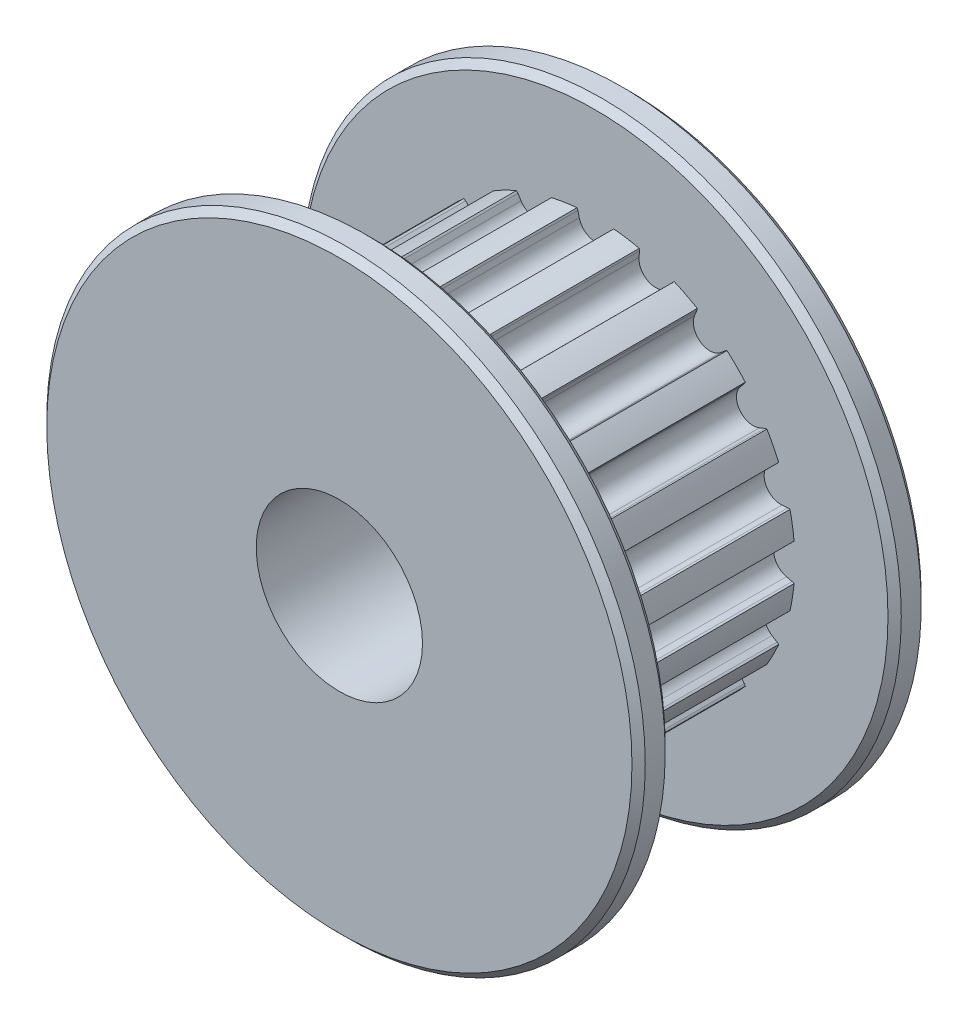
SolidWorks part; units mm, degrees
ref_plane "Спереди" through (0, 0, 0) normal (0, 0, 1) x (1, 0, 0)
ref_plane "Сверху" through (0, 0, 0) normal (0, 1, 0) x (1, 0, 0)
ref_plane "Справа" through (0, 0, 0) normal (1, 0, 0) x (0, 0, -1)
ref_plane "Плоскость1" through (0, 0, 0) normal (0, -1, 0) x (1, 0, 0)
sketch "Эскиз1" plane through (0, 0, 0) normal (0, -1, 0) x (1, 0, 0)
  line L0 (9, -3.35) -> (0, -3.35)
  line L1 (0, -3.35) -> (0, -4.35)
  line L2 (0, -4.35) -> (9, -4.35)
  line L3 (9, -4.35) -> (9, -3.35)
  line L4 (0, -3.35) -> (0, -4.35) construction
revolve "Повернуть1" add sketch "Эскиз1" angle 360 about L4
sketch "Эскиз2" plane through (0, 0, -3.35) normal (0, 0, 1) x (1, 0, 0)
  line L0 (5.4631, 2.3299) -> (5.3126, 2.2369)
  line L1 (5.6128, 1.313) -> (5.7893, 1.3262)
  line L2 (5.9157, 0.5277) -> (5.7438, 0.4857)
  line L3 (5.7438, -0.4857) -> (5.9157, -0.5277)
  line L4 (5.7893, -1.3262) -> (5.6128, -1.313)
  line L5 (5.3126, -2.2369) -> (5.4631, -2.3299)
  line L6 (5.0961, -3.0502) -> (4.9323, -2.9832)
  line L7 (4.3614, -3.7691) -> (4.4757, -3.9041)
  line L8 (3.9041, -4.4757) -> (3.7691, -4.3614)
  line L9 (2.9832, -4.9323) -> (3.0502, -5.0961)
  line L10 (2.3299, -5.4631) -> (2.2369, -5.3126)
  line L11 (1.313, -5.6128) -> (1.3262, -5.7893)
  line L12 (0.5277, -5.9157) -> (0.4857, -5.7438)
  line L13 (-0.4857, -5.7438) -> (-0.5277, -5.9157)
  line L14 (-1.3262, -5.7893) -> (-1.313, -5.6128)
  line L15 (-2.2369, -5.3126) -> (-2.3299, -5.4631)
  line L16 (-3.0502, -5.0961) -> (-2.9832, -4.9323)
  line L17 (-3.7691, -4.3614) -> (-3.9041, -4.4757)
  line L18 (-4.4757, -3.9041) -> (-4.3614, -3.7691)
  line L19 (-4.9323, -2.9832) -> (-5.0961, -3.0502)
  line L20 (-5.4631, -2.3299) -> (-5.3126, -2.2369)
  line L21 (-5.6128, -1.313) -> (-5.7893, -1.3262)
  line L22 (-5.9157, -0.5277) -> (-5.7438, -0.4857)
  line L23 (-5.7438, 0.4857) -> (-5.9157, 0.5277)
  line L24 (-5.7893, 1.3262) -> (-5.6128, 1.313)
  line L25 (-5.3126, 2.2369) -> (-5.4631, 2.3299)
  line L26 (-5.0961, 3.0502) -> (-4.9323, 2.9832)
  line L27 (-4.3614, 3.7691) -> (-4.4757, 3.9041)
  line L28 (-3.9041, 4.4757) -> (-3.7691, 4.3614)
  line L29 (-2.9832, 4.9323) -> (-3.0502, 5.0961)
  line L30 (-2.3299, 5.4631) -> (-2.2369, 5.3126)
  line L31 (-1.313, 5.6128) -> (-1.3262, 5.7893)
  line L32 (-0.5277, 5.9157) -> (-0.4857, 5.7438)
  line L33 (0.4857, 5.7438) -> (0.5277, 5.9157)
  line L34 (1.3262, 5.7893) -> (1.313, 5.6128)
  line L35 (2.2369, 5.3126) -> (2.3299, 5.4631)
  line L36 (3.0502, 5.0961) -> (2.9832, 4.9323)
  line L37 (3.7691, 4.3614) -> (3.9041, 4.4757)
  line L38 (4.4757, 3.9041) -> (4.3614, 3.7691)
  line L39 (4.9323, 2.9832) -> (5.0961, 3.0502)
  arc A0 (5.0961, 3.0502) -> (5.1583, 3.0647) centre (5.1719, 2.8652) cw
  arc A1 (5.1583, 3.0647) -> (5.5113, 2.3717) centre (0, 0) cw
  arc A2 (5.5113, 2.3717) -> (5.4631, 2.3299) centre (5.3579, 2.5001) cw
  arc A3 (5.3126, 2.2369) -> (5.6128, 1.313) centre (5.5756, 1.8116) ccw
  arc A4 (5.7893, 1.3262) -> (5.8528, 1.3207) centre (5.8041, 1.1267) cw
  arc A5 (5.8528, 1.3207) -> (5.9745, 0.5526) centre (0, 0) cw
  arc A6 (5.9745, 0.5526) -> (5.9157, 0.5277) centre (5.8683, 0.722) cw
  arc A7 (5.7438, 0.4857) -> (5.7438, -0.4857) centre (5.8625, 0) ccw
  arc A8 (5.9157, -0.5277) -> (5.9745, -0.5526) centre (5.8683, -0.722) cw
  arc A9 (5.9745, -0.5526) -> (5.8528, -1.3207) centre (0, 0) cw
  arc A10 (5.8528, -1.3207) -> (5.7893, -1.3262) centre (5.8041, -1.1267) cw
  arc A11 (5.6128, -1.313) -> (5.3126, -2.2369) centre (5.5756, -1.8116) ccw
  arc A12 (5.4631, -2.3299) -> (5.5113, -2.3717) centre (5.3579, -2.5001) cw
  arc A13 (5.5113, -2.3717) -> (5.1583, -3.0647) centre (0, 0) cw
  arc A14 (5.1583, -3.0647) -> (5.0961, -3.0502) centre (5.1719, -2.8652) cw
  arc A15 (4.9323, -2.9832) -> (4.3614, -3.7691) centre (4.7429, -3.4459) ccw
  arc A16 (4.4757, -3.9041) -> (4.5087, -3.9588) centre (4.3231, -4.0334) cw
  arc A17 (4.5087, -3.9588) -> (3.9588, -4.5087) centre (0, 0) cw
  arc A18 (3.9588, -4.5087) -> (3.9041, -4.4757) centre (4.0334, -4.3231) cw
  arc A19 (3.7691, -4.3614) -> (2.9832, -4.9323) centre (3.4459, -4.7429) ccw
  arc A20 (3.0502, -5.0961) -> (3.0647, -5.1583) centre (2.8652, -5.1719) cw
  arc A21 (3.0647, -5.1583) -> (2.3717, -5.5113) centre (0, 0) cw
  arc A22 (2.3717, -5.5113) -> (2.3299, -5.4631) centre (2.5001, -5.3579) cw
  arc A23 (2.2369, -5.3126) -> (1.313, -5.6128) centre (1.8116, -5.5756) ccw
  arc A24 (1.3262, -5.7893) -> (1.3207, -5.8528) centre (1.1267, -5.8041) cw
  arc A25 (1.3207, -5.8528) -> (0.5526, -5.9745) centre (0, 0) cw
  arc A26 (0.5526, -5.9745) -> (0.5277, -5.9157) centre (0.722, -5.8683) cw
  arc A27 (0.4857, -5.7438) -> (-0.4857, -5.7438) centre (0, -5.8625) ccw
  arc A28 (-0.5277, -5.9157) -> (-0.5526, -5.9745) centre (-0.722, -5.8683) cw
  arc A29 (-0.5526, -5.9745) -> (-1.3207, -5.8528) centre (0, 0) cw
  arc A30 (-1.3207, -5.8528) -> (-1.3262, -5.7893) centre (-1.1267, -5.8041) cw
  arc A31 (-1.313, -5.6128) -> (-2.2369, -5.3126) centre (-1.8116, -5.5756) ccw
  arc A32 (-2.3299, -5.4631) -> (-2.3717, -5.5113) centre (-2.5001, -5.3579) cw
  arc A33 (-2.3717, -5.5113) -> (-3.0647, -5.1583) centre (0, 0) cw
  arc A34 (-3.0647, -5.1583) -> (-3.0502, -5.0961) centre (-2.8652, -5.1719) cw
  arc A35 (-2.9832, -4.9323) -> (-3.7691, -4.3614) centre (-3.4459, -4.7429) ccw
  arc A36 (-3.9041, -4.4757) -> (-3.9588, -4.5087) centre (-4.0334, -4.3231) cw
  arc A37 (-3.9588, -4.5087) -> (-4.5087, -3.9588) centre (0, 0) cw
  arc A38 (-4.5087, -3.9588) -> (-4.4757, -3.9041) centre (-4.3231, -4.0334) cw
  arc A39 (-4.3614, -3.7691) -> (-4.9323, -2.9832) centre (-4.7429, -3.4459) ccw
  arc A40 (-5.0961, -3.0502) -> (-5.1583, -3.0647) centre (-5.1719, -2.8652) cw
  arc A41 (-5.1583, -3.0647) -> (-5.5113, -2.3717) centre (0, 0) cw
  arc A42 (-5.5113, -2.3717) -> (-5.4631, -2.3299) centre (-5.3579, -2.5001) cw
  arc A43 (-5.3126, -2.2369) -> (-5.6128, -1.313) centre (-5.5756, -1.8116) ccw
  arc A44 (-5.7893, -1.3262) -> (-5.8528, -1.3207) centre (-5.8041, -1.1267) cw
  arc A45 (-5.8528, -1.3207) -> (-5.9745, -0.5526) centre (0, 0) cw
  arc A46 (-5.9745, -0.5526) -> (-5.9157, -0.5277) centre (-5.8683, -0.722) cw
  arc A47 (-5.7438, -0.4857) -> (-5.7438, 0.4857) centre (-5.8625, 0) ccw
  arc A48 (-5.9157, 0.5277) -> (-5.9745, 0.5526) centre (-5.8683, 0.722) cw
  arc A49 (-5.9745, 0.5526) -> (-5.8528, 1.3207) centre (0, 0) cw
  arc A50 (-5.8528, 1.3207) -> (-5.7893, 1.3262) centre (-5.8041, 1.1267) cw
  arc A51 (-5.6128, 1.313) -> (-5.3126, 2.2369) centre (-5.5756, 1.8116) ccw
  arc A52 (-5.4631, 2.3299) -> (-5.5113, 2.3717) centre (-5.3579, 2.5001) cw
  arc A53 (-5.5113, 2.3717) -> (-5.1583, 3.0647) centre (0, 0) cw
  arc A54 (-5.1583, 3.0647) -> (-5.0961, 3.0502) centre (-5.1719, 2.8652) cw
  arc A55 (-4.9323, 2.9832) -> (-4.3614, 3.7691) centre (-4.7429, 3.4459) ccw
  arc A56 (-4.4757, 3.9041) -> (-4.5087, 3.9588) centre (-4.3231, 4.0334) cw
  arc A57 (-4.5087, 3.9588) -> (-3.9588, 4.5087) centre (0, 0) cw
  arc A58 (-3.9588, 4.5087) -> (-3.9041, 4.4757) centre (-4.0334, 4.3231) cw
  arc A59 (-3.7691, 4.3614) -> (-2.9832, 4.9323) centre (-3.4459, 4.7429) ccw
  arc A60 (-3.0502, 5.0961) -> (-3.0647, 5.1583) centre (-2.8652, 5.1719) cw
  arc A61 (-3.0647, 5.1583) -> (-2.3717, 5.5113) centre (0, 0) cw
  arc A62 (-2.3717, 5.5113) -> (-2.3299, 5.4631) centre (-2.5001, 5.3579) cw
  arc A63 (-2.2369, 5.3126) -> (-1.313, 5.6128) centre (-1.8116, 5.5756) ccw
  arc A64 (-1.3262, 5.7893) -> (-1.3207, 5.8528) centre (-1.1267, 5.8041) cw
  arc A65 (-1.3207, 5.8528) -> (-0.5526, 5.9745) centre (0, 0) cw
  arc A66 (-0.5526, 5.9745) -> (-0.5277, 5.9157) centre (-0.722, 5.8683) cw
  arc A67 (-0.4857, 5.7438) -> (0.4857, 5.7438) centre (0, 5.8625) ccw
  arc A68 (0.5277, 5.9157) -> (0.5526, 5.9745) centre (0.722, 5.8683) cw
  arc A69 (0.5526, 5.9745) -> (1.3207, 5.8528) centre (0, 0) cw
  arc A70 (1.3207, 5.8528) -> (1.3262, 5.7893) centre (1.1267, 5.8041) cw
  arc A71 (1.313, 5.6128) -> (2.2369, 5.3126) centre (1.8116, 5.5756) ccw
  arc A72 (2.3299, 5.4631) -> (2.3717, 5.5113) centre (2.5001, 5.3579) cw
  arc A73 (2.3717, 5.5113) -> (3.0647, 5.1583) centre (0, 0) cw
  arc A74 (3.0647, 5.1583) -> (3.0502, 5.0961) centre (2.8652, 5.1719) cw
  arc A75 (2.9832, 4.9323) -> (3.7691, 4.3614) centre (3.4459, 4.7429) ccw
  arc A76 (3.9041, 4.4757) -> (3.9588, 4.5087) centre (4.0334, 4.3231) cw
  arc A77 (3.9588, 4.5087) -> (4.5087, 3.9588) centre (0, 0) cw
  arc A78 (4.5087, 3.9588) -> (4.4757, 3.9041) centre (4.3231, 4.0334) cw
  arc A79 (4.3614, 3.7691) -> (4.9323, 2.9832) centre (4.7429, 3.4459) ccw
extrude "Бобышка-Вытянуть1" add sketch "Эскиз2" along normal blind 6.7
ref_plane "Плоскость2" through (0, 0, 3.35) normal (0, 0, -1) x (-1, 0, 0)
sketch "Эскиз3" plane through (0, 0, 3.35) normal (0, 0, -1) x (-1, 0, 0)
  circle A0 centre (0, 0) radius 9
extrude "Бобышка-Вытянуть2" add sketch "Эскиз3" against normal blind 1
hole_wizard "Диаметр отверстия Ø5.0 (5)1" positions "Эскиз5" profile "Эскиз4" hole size "Ø5.0" standard "Ansi Metric"
sketch "Эскиз5" plane through (0, 0, 4.35) normal (0, 0, 1) x (1, 0, 0)
  point P0 (0, 0)
sketch "Эскиз4" plane through (0, 0, 4.35) normal (1, 0, 0) x (0, -1, 0)
  line L0 (0, 0) -> (0, 8.7)
  line L1 (0, 8.7) -> (2.5, 8.7)
  line L2 (2.5, 8.7) -> (2.5, 0)
  line L5 (2.5, 0) -> (0, 0)
  line L11 (0, -6.35) -> (0, 107.95) construction
  dimension "Диаметр сквозного отверстия" = 5
  dimension "Глубина сквозного отверстия" = 8.7
chamfer "Фаска1" distance 0.2 angle 45 4 edges at (-9, 0, -3.35) (9, 0, 4.35) (9, 0, 3.35) (-9, 0, -4.35)
